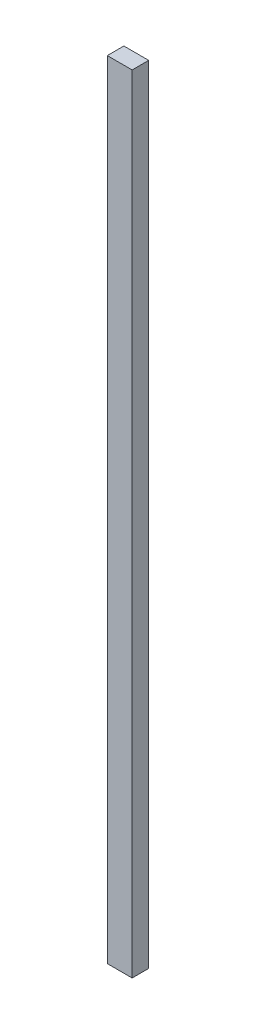
SolidWorks part; units mm, degrees
ref_plane "Front Plane" through (0, 0, 0) normal (0, 0, 1) x (1, 0, 0)
ref_plane "Top Plane" through (0, 0, 0) normal (0, 1, 0) x (1, 0, 0)
ref_plane "Right Plane" through (0, 0, 0) normal (1, 0, 0) x (0, 0, -1)
sketch "Sketch1" plane through (0, 0, -41.3066) normal (0, 0, -1) x (-1, 0, 0)
  line L0 (-29, 224.6315) -> (29, 224.6315) construction
  line L1 (-6, 604.1315) -> (6, 604.1315)
  line L2 (-6, 604.1315) -> (-6, 224.6315)
  line L3 (-6, 224.6315) -> (6, 224.6315)
  line L4 (6, 604.1315) -> (6, 224.6315)
  line L5 (-6, 604.1315) -> (6, 224.6315) construction
  line L6 (-6, 224.6315) -> (6, 604.1315) construction
  line L7 (-29, 224.6315) -> (29, 224.6315) construction
  line L8 (-29, 604.1315) -> (29, 604.1315) construction
  line L9 (-29, 604.1315) -> (29, 604.1315) construction
  line L10 (0, 604.1315) -> (0, 224.6315) construction
  point P0 (0, 414.3815)
  dimension "D1" = 12
extrude "Boss-Extrude1" add sketch "Sketch1" along normal blind 8
